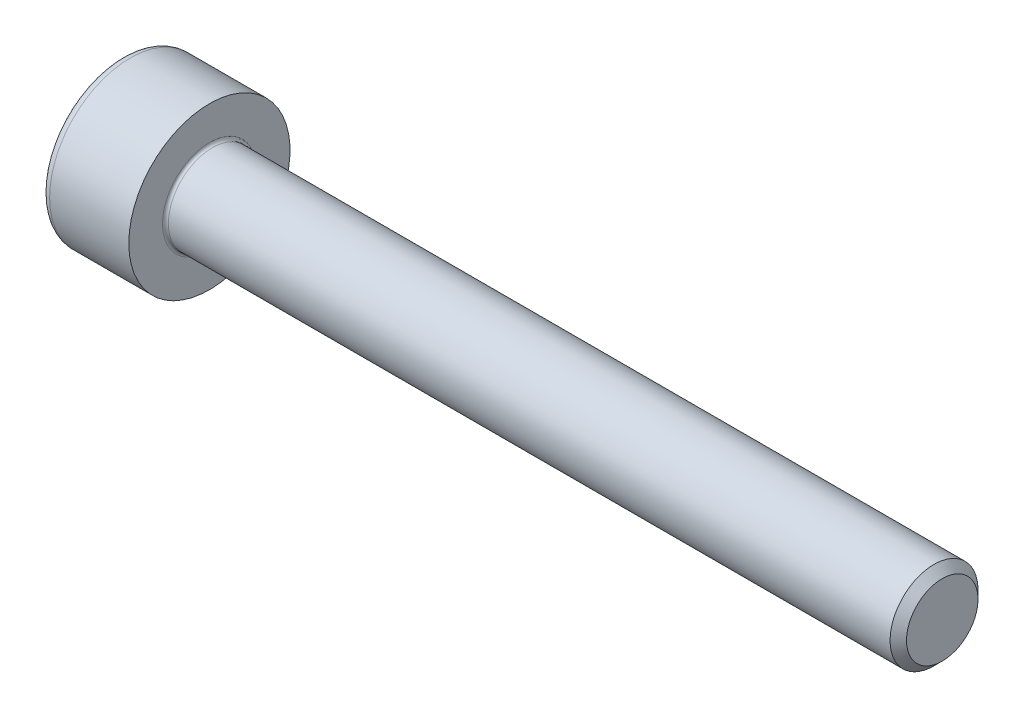
SolidWorks part; units mm, degrees
revolve "Base-Revolve" add sketch "BodySke"
sketch "BodySke" plane through (0, 0, 0) normal (0, 0, 1) x (1, 0, 0)
  line L0 (0, 0) -> (0, 2.75)
  line L1 (0, 2.75) -> (3, 2.75)
  line L2 (3, 2.75) -> (3, 1.5)
  line L3 (3, 1.5) -> (27.7195, 1.5)
  line L4 (28, 1.2195) -> (28, 0)
  line L5 (28, 0) -> (0, 0)
  line L6 (-31.75, 0) -> (127, 0) construction
  line L8 (28, 1.2195) -> (27.7195, 1.5)
  line L10 (28, -1.2195) -> (27.7195, -1.5) construction
  line L11 (3.5, 9.525) -> (3.5, 3.175) construction
  line L12 (10, 9.525) -> (10, 3.175) construction
  line L13 (-32, 9.525) -> (-32, 3.175) construction
  dimension "Head_ht" = 3
  dimension "Length" = 25
  dimension "Body_ch_ang" = 45
  dimension "Diameter" = 3
  dimension "Minor_dia" = 2.439
  dimension "Advance" = 0.5
  dimension "Thread_nom" = 18
  dimension "Thread_length" = 60
  dimension "Head_dia" = 5.5
cosmetic thread "ThreadCosmetic" [suppressed]
fillet "Fillet1" radius 0.1 1 edges at (3, 0, 1.5)
fillet "Fillet2" radius 0.3 1 edges at (0, 0, 2.75)
ref_plane "Plane1" through (0, 0, 0) normal (0, 0, 1) x (1, 0, 0)
ref_plane "Plane2" through (0, 0, 0) normal (0, 1, 0) x (1, 0, 0)
ref_plane "Plane3" through (0, 0, 0) normal (1, 0, 0) x (0, 0, -1)
sketch "Sketch2" plane through (0, 0, 0) normal (0, 0, 1) x (1, 0, 0)
  line L0 (0, 1.26) -> (1.3, 1.26)
  line L1 (1.3, 1.26) -> (2.0275, 0)
  line L2 (-31.75, 0) -> (127, 0) construction
  line L3 (2.0275, 0) -> (0, 0)
  line L4 (0, 0) -> (0, 1.26)
  line L6 (0, 0) -> (47.625, 0) construction
  dimension "D1" = 1.26
  dimension "D2" = 60
  dimension "Depth" = 1.3
revolve "Hex-PreBroach" cut sketch "Sketch2" angle 360 about L6
sketch "Sketch3" plane through (0, 0, 0) normal (-1, 0, 0) x (0, 0.5, 0.866)
  line L0 (0.7275, 1.26) -> (-0.7275, 1.26)
  line L1 (-0.7275, 1.26) -> (-1.4549, 0)
  line L2 (0.7275, 1.26) -> (1.4549, 0)
  line L3 (0.7275, -1.26) -> (1.4549, 0)
  line L4 (0.7275, -1.26) -> (-0.7275, -1.26)
  line L5 (-0.7275, -1.26) -> (-1.4549, 0)
  dimension "D1" = 1.26
  dimension "D2" = 1.26
  dimension "Hex_size" = 2.52
extrude "Hex" cut sketch "Sketch3" against normal blind 1.3
sketch "ThdSchSke" plane through (0, 0, 0) normal (0, 0, 1) x (1, 0, 0)
  line L0 (10, -1.2195) -> (9.8036, -1.5)
  line L1 (10, -1.2195) -> (10.1964, -1.5)
  line L2 (10.1964, -1.5) -> (10.1964, -1.875)
  line L3 (-3.175, 0) -> (5.1513, 0) construction
  line L4 (0, 2.45) -> (0, -2.45) construction
  line L5 (10.1964, -1.875) -> (9.8036, -1.875)
  line L6 (9.8036, -1.875) -> (9.8036, -1.5)
  dimension "Thread_minor" = 2.439
  dimension "Diameter" = 3
  dimension "Start" = 10
revolve "ThreadSchematic" [suppressed] cut sketch "ThdSchSke" angle 360 about L3
pattern_linear "ThdSchPat" [suppressed]
equation "\"D2@Sketch3\" = \"Hex_size@Sketch3\" / 2"
equation "\"D1@Sketch3\" = \"Hex_size@Sketch3\" / 2"
equation "\"D1@Sketch2\" = \"Hex_size@Sketch3\" / 2"
equation "\"Thread_minor@ThreadCosmetic\"  =  \"Minor_dia@BodySke\""
equation "\"Depth@Sketch2\" =  \"Key_eng@Hex\""
equation "\"Thread_length@ThreadCosmetic\" = ((sgn( (\"Length@BodySke\" - \"Advance@BodySke\" * 3.0) - \"Thread_nom@BodySke\" )-1)*( (\"Length@BodySke\" - \"Advance@BodySke\" * 3.0) - \"Thread_nom@BodySke\" ))/-2+ \"Thread_nom@BodySke\""
equation "\"Thread_minor@ThdSchSke\" = \"Minor_dia@BodySke\""
equation "\"Diameter@ThdSchSke\" = \"Diameter@BodySke\""
equation "\"Overcut@ThdSchSke\" = \"Diameter@BodySke\" * 1.25"
equation "\"Start@ThdSchSke\" = \"Head_ht@BodySke\" + \"Length@BodySke\" - \"Thread_length@ThreadCosmetic\"  '---Non-countersunk---"
equation "\"Num_threads@ThdSchPat\" = int( \"Thread_length@ThreadCosmetic\" / \"Advance@BodySke\" + 0.999 )  + 1"
equation "\"Advance@ThdSchPat\" = \"Thread_length@ThreadCosmetic\" /  (\"Num_threads@ThdSchPat\" - 1) 'relax it"
equation "\"Num_threads@ThdSchPat\" = \"Num_threads@ThdSchPat\" - sgn( \"Num_threads@ThdSchPat\" - 1) '---chamfered tips only---"
